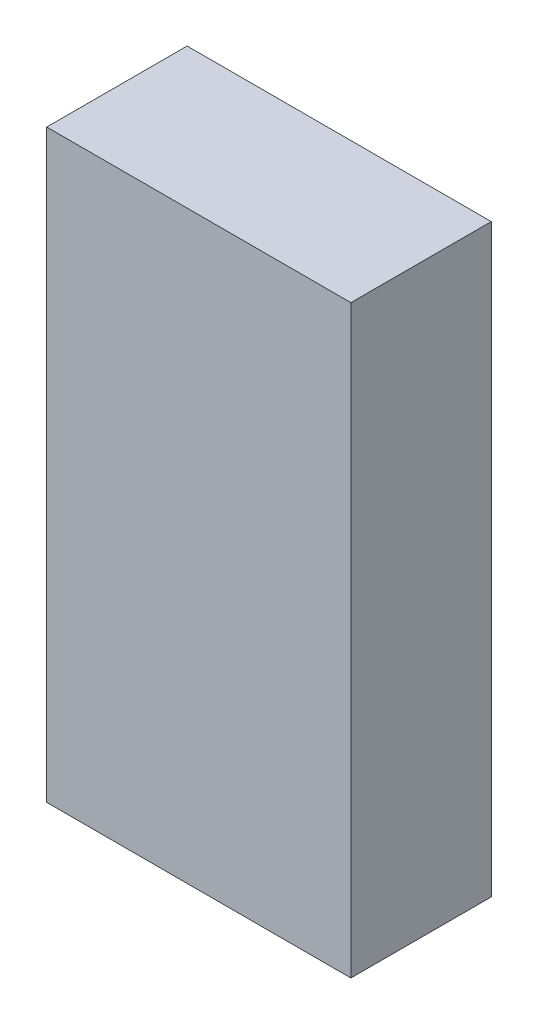
SolidWorks part; units mm, degrees
ref_plane "Ebene vorne" through (0, 0, 0) normal (0, 0, 1) x (1, 0, 0)
ref_plane "Ebene oben" through (0, 0, 0) normal (0, 1, 0) x (1, 0, 0)
ref_plane "Ebene rechts" through (0, 0, 0) normal (1, 0, 0) x (0, 0, -1)
sketch "Skizze1" plane through (0, 0, 0) normal (0, 0, 1) x (1, 0, 0)
  line L1 (0, 0) -> (26, 0)
  line L2 (0, 0) -> (0, 50)
  line L3 (0, 50) -> (26, 50)
  line L4 (26, 0) -> (26, 50)
  dimension "D1" = 50
  dimension "D2" = 26
extrude "Aufsatz-Linear austragen1" add sketch "Skizze1" along normal blind 12
